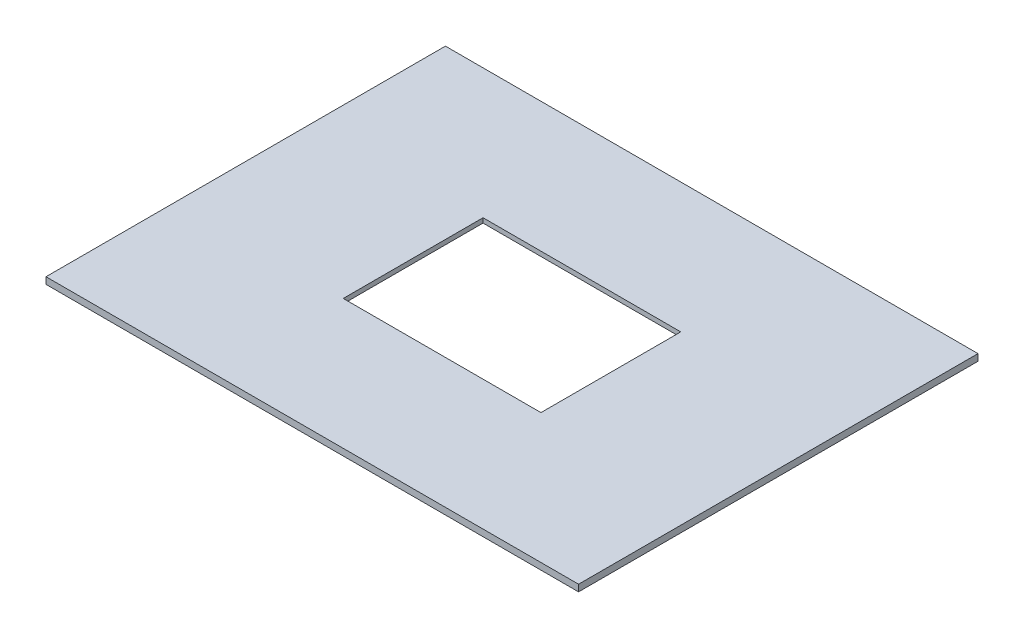
SolidWorks part; units mm, degrees
ref_plane "Front Plane" through (0, 0, 0) normal (0, 0, 1) x (1, 0, 0)
ref_plane "Top Plane" through (0, 0, 0) normal (0, 1, 0) x (1, 0, 0)
ref_plane "Right Plane" through (0, 0, 0) normal (1, 0, 0) x (0, 0, -1)
sketch "Sketch1" plane through (0, 0, 0) normal (0, 1, 0) x (1, 0, 0)
  line L1 (-148.5, -105) -> (148.5, -105)
  line L2 (-148.5, -105) -> (-148.5, 105)
  line L3 (-148.5, 105) -> (148.5, 105)
  line L4 (148.5, -105) -> (148.5, 105)
  line L5 (-148.5, -105) -> (148.5, 105) construction
  line L6 (-148.5, 105) -> (148.5, -105) construction
  line L7 (-400, -300) -> (400, -300)
  line L8 (-400, -300) -> (-400, 300)
  line L9 (-400, 300) -> (400, 300)
  line L10 (400, -300) -> (400, 300)
  line L11 (-400, -300) -> (400, 300) construction
  line L12 (-400, 300) -> (400, -300) construction
  point P0 (0, 0)
  point P6 (0, 0)
  dimension "D1" = 800
  dimension "brede" = 297
  dimension "D2" = 600
  dimension "højde" = 210
extrude "Extrude1" add sketch "Sketch1" against normal blind 10
sketch "Sketch2" plane through (0, -10, 0) normal (0, -1, 0) x (1, 0, 0)
  line L0 (-148.5, -115) -> (-148.5, 115)
  line L1 (-148.5, -105) -> (-148.5, 105) construction
  line L2 (-153.5, 115) -> (-153.5, -115)
  line L3 (-148.5, -115) -> (-153.5, -115) construction
  line L4 (148.5, -105) -> (-148.5, -105) construction
  line L5 (-148.5, 115) -> (-153.5, 115) construction
  line L6 (-148.5, 105) -> (148.5, 105) construction
  arc A0 (-153.5, -115) -> (-148.5, -115) centre (-151, -115) ccw
  arc A1 (-153.5, 115) -> (-148.5, 115) centre (-151, 115) cw
  point P6 (-151, -115)
  dimension "D1" = 5
  dimension "D2" = 10
  dimension "D3" = 10
extrude "Extrude2" cut sketch "Sketch2" against normal blind 3
mirror "Mirror1" about plane through (0, 0, 0) normal (1, 0, 0) of "Extrude2"
sketch "Sketch3" plane through (0, -10, 0) normal (0, -1, 0) x (1, 0, 0)
  line L1 (-148.5, 105) -> (148.5, 105)
  line L2 (-148.5, 105) -> (-148.5, 110)
  line L3 (-148.5, 110) -> (148.5, 110)
  line L4 (148.5, 105) -> (148.5, 110)
  line L5 (148.5, 105) -> (148.5, 115) construction
  dimension "D1" = 5
extrude "Extrude3" cut sketch "Sketch3" against normal blind 3
mirror "Mirror2" about plane through (0, 0, 0) normal (0, 0, 1) of "Extrude3"
